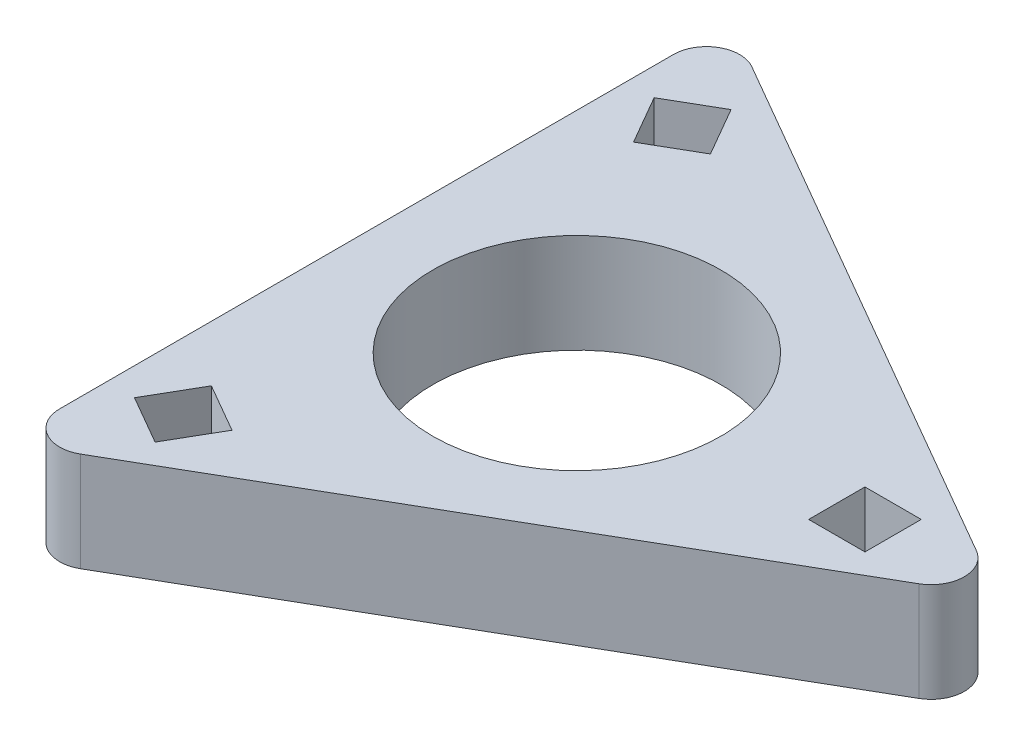
SolidWorks part; units mm, degrees
material "ABS"
ref_plane "Front Plane" through (0, 0, 0) normal (0, 0, 1) x (1, 0, 0)
ref_plane "Top Plane" through (0, 0, 0) normal (0, 1, 0) x (1, 0, 0)
ref_plane "Right Plane" through (0, 0, 0) normal (1, 0, 0) x (0, 0, -1)
sketch "Sketch2" plane through (0, 0, 0) normal (0, 1, 0) x (1, 0, 0)
  line L4 (184.9421, 95.4106) -> (89.6793, 150.4106)
  line L5 (89.6793, 150.4106) -> (89.6793, 40.4106)
  line L6 (89.6793, 40.4106) -> (184.9421, 95.4106)
  line L10 (105.485, 59.2867) -> (98.1237, 63.5367)
  line L11 (98.1237, 63.5367) -> (93.8737, 56.1755)
  line L12 (93.8737, 56.1755) -> (101.235, 51.9255)
  line L13 (101.235, 51.9255) -> (105.485, 59.2867)
  line L14 (169.1921, 99.6606) -> (160.6921, 99.6606)
  line L15 (160.6921, 99.6606) -> (160.6921, 91.1606)
  line L16 (160.6921, 91.1606) -> (169.1921, 91.1606)
  line L17 (169.1921, 91.1606) -> (169.1921, 99.6606)
  line L18 (105.485, 131.5345) -> (101.235, 138.8957)
  line L19 (101.235, 138.8957) -> (93.8737, 134.6457)
  line L20 (93.8737, 134.6457) -> (98.1237, 127.2845)
  line L21 (98.1237, 127.2845) -> (105.485, 131.5345)
  circle A1 centre (121.4336, 95.4106) radius 31.7543 construction
  circle A2 centre (121.4336, 95.4106) radius 21.7543
  circle A3 centre (99.6793, 57.7311) radius 4.25 construction
  circle A4 centre (164.9421, 95.4106) radius 4.25 construction
  circle A5 centre (99.6793, 133.0901) radius 4.25 construction
  dimension "D4" = 8.5
  dimension "D2" = 10
  dimension "D12" = 110
  dimension "D3" = 30
  dimension "D5" = 30
  dimension "D6" = 8.5
  dimension "D7" = 30
  dimension "D8" = 8.5
  dimension "D9" = 20
  dimension "D10" = 20
  dimension "D11" = 20
extrude "Boss-Extrude2" add sketch "Sketch2" along normal blind 15
fillet "Fillet2" radius 5 3 edges at (89.6793, 7.5, -150.4106) (184.9421, 7.5, -95.4106) (89.6793, 7.5, -40.4106)
